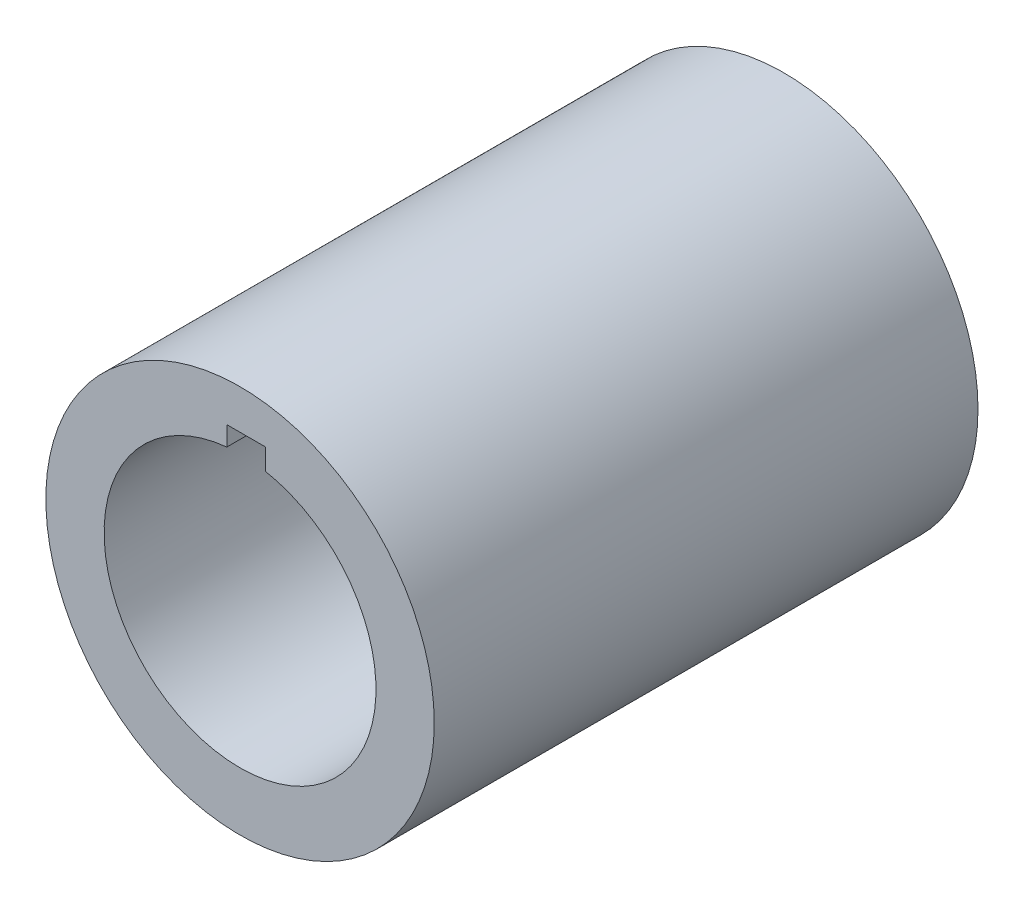
SolidWorks part; units mm, degrees
ref_plane "Front Plane" through (0, 0, 0) normal (0, 0, 1) x (1, 0, 0)
ref_plane "Top Plane" through (0, 0, 0) normal (0, 1, 0) x (1, 0, 0)
ref_plane "Right Plane" through (0, 0, 0) normal (1, 0, 0) x (0, 0, -1)
sketch "Sketch1" plane through (0, 0, 0) normal (0, 0, 1) x (1, 0, 0)
  line L0 (-0.3408, 3.4834) -> (-0.3408, 3.9834)
  line L1 (-0.3408, 3.9834) -> (0.6592, 3.9834)
  line L2 (0.6592, 3.9834) -> (0.6592, 3.4374)
  circle A0 centre (0, 0) radius 5
  arc A1 (-0.3408, 3.4834) -> (0.6592, 3.4374) centre (0, 0) ccw
extrude "Boss-Extrude1" add sketch "Sketch1" along normal blind 14
